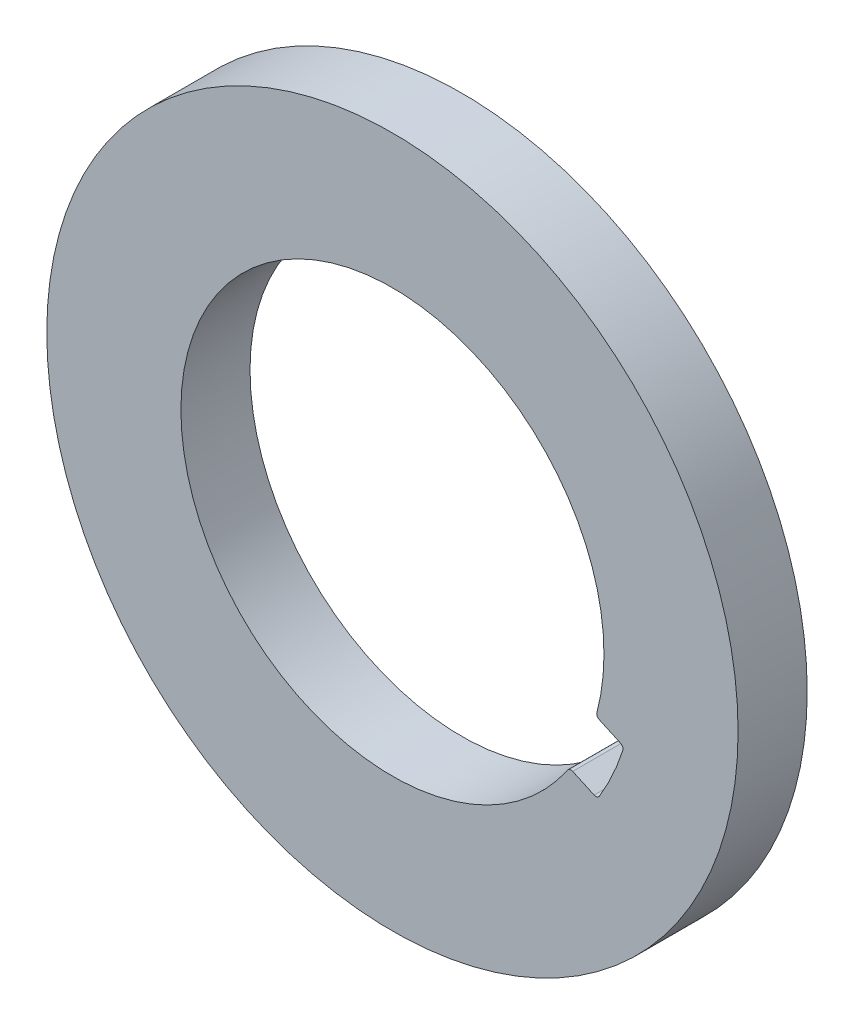
SolidWorks part; units mm, degrees
material "Chêne"
ref_plane "Plan de face" through (0, 0, 0) normal (0, 0, 1) x (1, 0, 0)
ref_plane "Plan de dessus" through (0, 0, 0) normal (0, 1, 0) x (1, 0, 0)
ref_plane "Plan de droite" through (0, 0, 0) normal (1, 0, 0) x (0, 0, -1)
sketch "Esquisse1" plane through (0, 0, 0) normal (0, 0, 1) x (1, 0, 0)
  line L0 (14.953, -4.2772) -> (16.5018, -4.9824)
  line L1 (13.0383, -8.4787) -> (14.587, -9.1845)
  arc A0 (12.6655, -8.5834) -> (14.7874, -3.9272) centre (0, 0) cw
  arc A1 (16.6631, -5.3471) -> (14.968, -9.0669) centre (0, 0) cw
  arc A2 (14.953, -4.2772) -> (14.7874, -3.9272) centre (15.0774, -4.0042) cw
  arc A3 (16.6631, -5.3471) -> (16.5018, -4.9824) centre (16.3774, -5.2555) ccw
  arc A4 (14.587, -9.1845) -> (14.968, -9.0669) centre (14.7114, -8.9115) ccw
  circle A5 centre (0, 0) radius 25
  arc A83 (13.0383, -8.4787) -> (12.6655, -8.5834) centre (12.9139, -8.7517) ccw
  point P116 (0, 0)
  point P374 (0, 0)
extrude "Boss.-Extru.1" add sketch "Esquisse1" along normal blind 5
